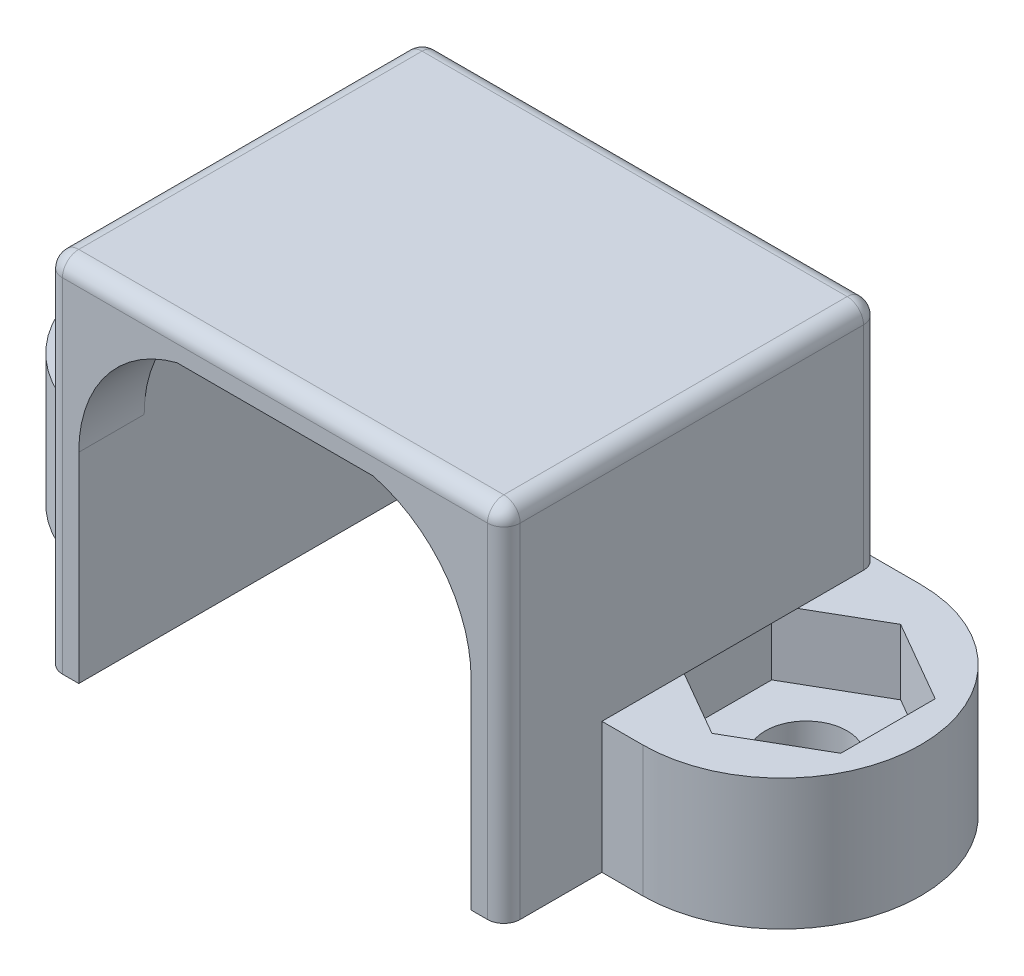
SolidWorks part; units mm, degrees
material "ABS"
ref_plane "Přední rovina" through (0, 0, 0) normal (0, 0, 1) x (1, 0, 0)
ref_plane "Horní rovina" through (0, 0, 0) normal (0, 1, 0) x (1, 0, 0)
ref_plane "Pravá rovina" through (0, 0, 0) normal (1, 0, 0) x (0, 0, -1)
sketch "Skica1" plane through (0, 0, 0) normal (0, 0, 1) x (1, 0, 0)
  line L0 (-12.5, 0) -> (-6, 0)
  line L1 (-6, 0) -> (-6, 10)
  line L2 (-6, 10) -> (6, 10)
  line L3 (-12.5, 0) -> (-12.5, 4)
  line L4 (-12.5, 4) -> (-7, 4)
  line L5 (-7, 4) -> (-7, 11)
  line L6 (-7, 11) -> (7, 11)
  line L7 (0, 0) -> (0, 11) construction
  line L8 (7, 4) -> (7, 11)
  line L9 (12.5, 4) -> (7, 4)
  line L10 (12.5, 0) -> (12.5, 4)
  line L11 (6, 0) -> (6, 10)
  line L12 (12.5, 0) -> (6, 0)
  point P15 (0, 10)
  dimension "D1" = 12
  dimension "D2" = 10
  dimension "D3" = 11
  dimension "D4" = 14
  dimension "D5" = 25
  dimension "D6" = 4
extrude "Přidat vysunutím1" add sketch "Skica1" along normal blind 11.5
sketch "Skica3" plane through (0, 4, 0) normal (0, 1, 0) x (1, 0, 0)
  line L0 (-7, 0) -> (-12.5, 0) construction
  line L1 (-12.5, -11.5) -> (-12.5, 0) construction
  line L2 (-8.25, 0) -> (-7, 0)
  line L3 (-7, 0) -> (7, 0)
  line L4 (7, 0) -> (-7, 0) construction
  line L5 (0, 0) -> (0, -11.5) construction
  line L6 (7, -11.5) -> (-7, -11.5) construction
  line L7 (-8.25, -8.5) -> (-7, -8.5)
  line L8 (-7, -11.5) -> (-7, 0) construction
  line L9 (-7, -8.5) -> (-7, -11.5)
  line L10 (-7, -11.5) -> (7, -11.5)
  line L11 (7, -8.5) -> (7, -11.5)
  line L12 (8.25, -8.5) -> (7, -8.5)
  line L13 (8.25, 0) -> (7, 0)
  arc A0 (-8.25, 0) -> (-8.25, -8.5) centre (-8.25, -4.25) ccw
  arc A1 (8.25, 0) -> (8.25, -8.5) centre (8.25, -4.25) cw
  dimension "D1" = 4.25
extrude "Odebrat vysunutím1" cut sketch "Skica3" against normal through all flip side to cut
sketch "Skica4" plane through (0, 4, 0) normal (0, 1, 0) x (1, 0, 0)
  line L0 (0, 0) -> (0, -11.5) construction
  line L1 (7, -11.5) -> (-7, -11.5) construction
  line L4 (-9, -4.25) -> (-4.4647, -4.25) construction
  line L5 (-7, 0) -> (-8.25, 0) construction
  line L6 (-8.25, -8.5) -> (-7, -8.5) construction
  circle A0 centre (-9, -4.25) radius 1.25
  circle A2 centre (9, -4.25) radius 1.25
  dimension "D1" = 18
  dimension "D2" = 2.5
extrude "Odebrat vysunutím2" cut sketch "Skica4" against normal through all
sketch "Skica5" plane through (0, 4, 0) normal (0, 1, 0) x (1, 0, 0)
  line L0 (0, 0) -> (0, -11.5) construction
  line L1 (-6.5, -5.6934) -> (-6.5, -2.8066)
  line L2 (-6.5, -2.8066) -> (-9, -1.3632)
  line L3 (-9, -1.3632) -> (-11.5, -2.8066)
  line L4 (-11.5, -2.8066) -> (-11.5, -5.6934)
  line L5 (-11.5, -5.6934) -> (-9, -7.1368)
  line L6 (-9, -7.1368) -> (-6.5, -5.6934)
  line L7 (7, -11.5) -> (-7, -11.5) construction
  line L8 (9, -7.1368) -> (6.5, -5.6934)
  line L9 (11.5, -5.6934) -> (9, -7.1368)
  line L10 (11.5, -2.8066) -> (11.5, -5.6934)
  line L11 (9, -1.3632) -> (11.5, -2.8066)
  line L12 (6.5, -2.8066) -> (9, -1.3632)
  line L13 (6.5, -5.6934) -> (6.5, -2.8066)
  circle A0 centre (-9, -4.25) radius 2.5 construction
  circle A1 centre (9, -4.25) radius 2.5 construction
  dimension "D1" = 5
extrude "Odebrat vysunutím3" cut sketch "Skica5" against normal blind 2
sketch "Skica6" plane through (0, 0, 11.5) normal (0, 0, 1) x (1, 0, 0)
  line L0 (-6, 10) -> (6, 10) construction
  line L1 (-6, 0) -> (-6, 10) construction
  line L2 (-6, 10) -> (-3, 10)
  line L3 (-6, 6.127) -> (-6, 10)
  line L4 (0, 0) -> (0, 14.3292) construction
  line L5 (6, 6.127) -> (6, 10)
  line L6 (6, 10) -> (3, 10)
  arc A0 (-6, 6.127) -> (-3, 10) centre (-2, 6.127) cw
  arc A1 (6, 6.127) -> (3, 10) centre (2, 6.127) ccw
  dimension "D1" = 4
  dimension "D2" = 3
extrude "Přidat vysunutím2" add sketch "Skica6" against normal blind 2
fillet "Zaoblit2" radius 0.5 8 edges at (7, 5.5, 11.5) (0, 11, 0) (0, 11, 11.5) (-7, 5.5, 11.5) (-7, 7.5, 0) (-7, 11, 5.75) (7, 7.5, 0) (7, 11, 5.75)
